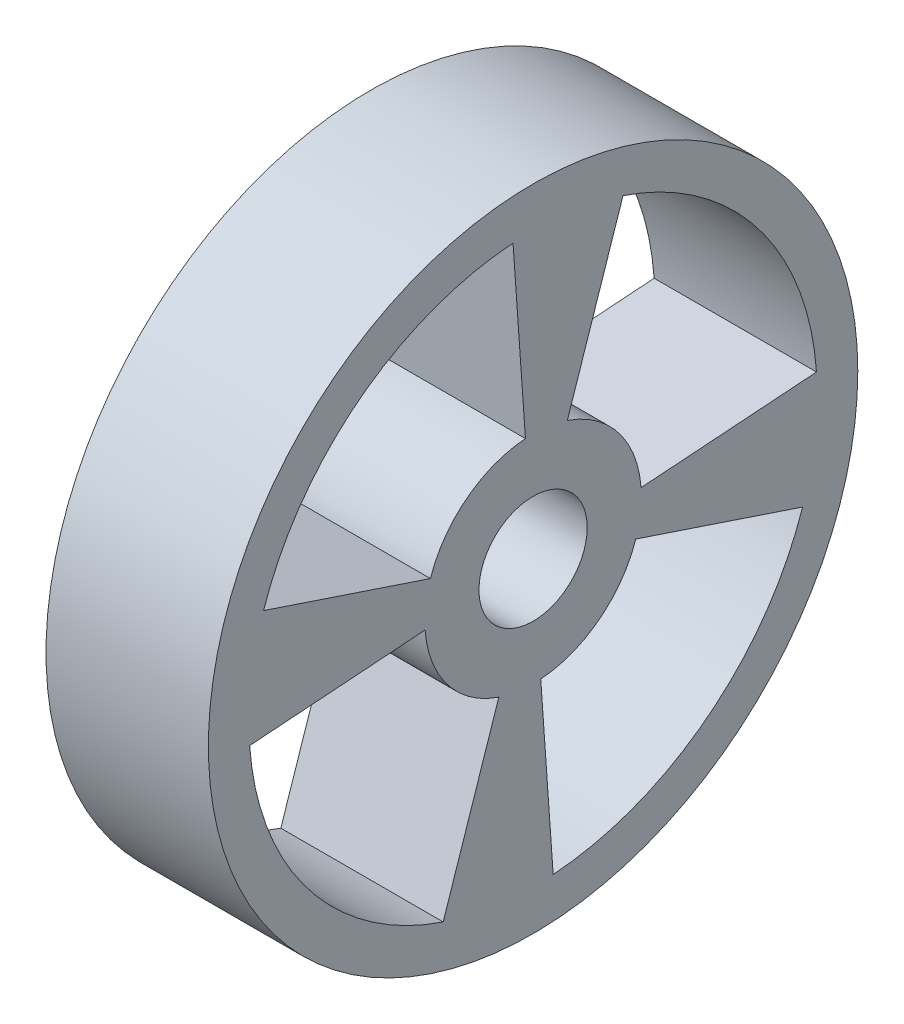
SolidWorks part; units mm, degrees
ref_plane "前视基准面" through (0, 0, 0) normal (0, 0, 1) x (1, 0, 0)
ref_plane "上视基准面" through (0, 0, 0) normal (0, 1, 0) x (1, 0, 0)
ref_plane "右视基准面" through (0, 0, 0) normal (1, 0, 0) x (0, 0, -1)
sketch "草图2" plane through (0, 0, 0) normal (1, 0, 0) x (0, 0, -1)
  line L0 (-0.2826, 3.99) -> (-0.7419, 10.4738)
  line L1 (1.2658, 3.7944) -> (3.3227, 9.9604)
  line L4 (3.99, 0.2826) -> (10.4738, 0.7419)
  line L5 (3.7944, -1.2658) -> (9.9604, -3.3227)
  line L8 (0.2826, -3.99) -> (0.7419, -10.4738)
  line L9 (-1.2658, -3.7944) -> (-3.3227, -9.9604)
  line L12 (-3.99, -0.2826) -> (-10.4738, -0.7419)
  line L13 (-3.7944, 1.2658) -> (-9.9604, 3.3227)
  line L31 (2.6215, 3.0212) -> (6.8815, 7.9306) [skipped]
  line L32 (3.5781, 1.788) -> (9.3926, 4.6935) [skipped]
  line L33 (3.0212, -2.6215) -> (7.9306, -6.8815) [skipped]
  line L34 (1.788, -3.5781) -> (4.6935, -9.3926) [skipped]
  line L35 (-2.6215, -3.0212) -> (-6.8815, -7.9306) [skipped]
  line L36 (-3.5781, -1.788) -> (-9.3926, -4.6935) [skipped]
  line L37 (-3.0212, 2.6215) -> (-7.9306, 6.8815) [skipped]
  line L38 (-1.788, 3.5781) -> (-4.6935, 9.3926) [skipped]
  circle A4 centre (0, 0) radius 2
  circle A5 centre (0, 0) radius 10.5
  circle A6 centre (0, 0) radius 12
  circle A7 centre (0, 0) radius 4
  point P42 (0, 0)
  dimension "D1" = 16
  dimension "D5" = 8.5
  dimension "D6" = 1.5
  dimension "D7" = 2
extrude "Boss-Extrude1" add sketch "草图2" along normal blind 6 contours A6 A5 | A7 L1 A5 L0 | A7 L5 A5 L4 | A7 L9 A5 L8 | A7 A4 | A7 L13 A5 L12
